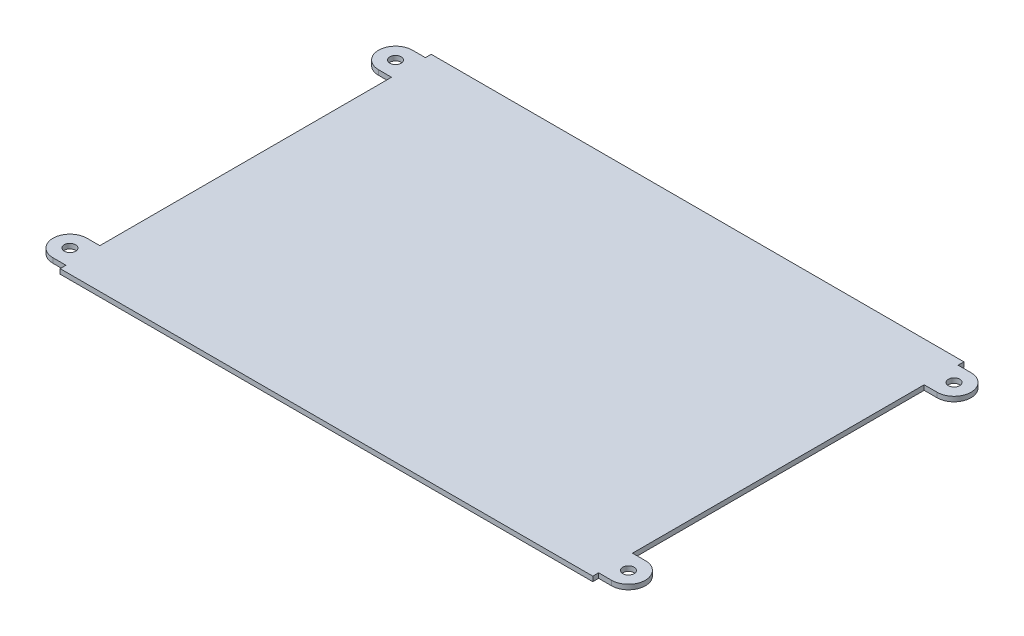
SolidWorks part; units mm, degrees
ref_plane "Front Plane" through (0, 0, 0) normal (0, 0, 1) x (1, 0, 0)
ref_plane "Top Plane" through (0, 0, 0) normal (0, 1, 0) x (1, 0, 0)
ref_plane "Right Plane" through (0, 0, 0) normal (1, 0, 0) x (0, 0, -1)
sketch "Sketch1" plane through (0, 0, 0) normal (0, 1, 0) x (1, 0, 0)
  line L0 (-82.45, -57.45) -> (82.45, -57.45)
  line L1 (-82.45, -57.45) -> (-82.45, 57.45)
  line L2 (82.45, -57.45) -> (82.45, 57.45)
  line L3 (-82.45, 57.45) -> (82.45, 57.45)
  line L4 (-82.45, -57.45) -> (82.45, 57.45) construction
  line L5 (82.45, -57.45) -> (-82.45, 57.45) construction
  point P1 (0, 0)
  dimension "D1" = 164.9
  dimension "D2" = 114.9
extrude "Boss-Extrude1" add sketch "Sketch1" along normal blind 1.5
sketch "Sketch2" plane through (0, 1.5, 0) normal (0, 1, 0) x (1, 0, 0)
  line L0 (-82.45, 57.45) -> (-82.45, -57.45) construction
  line L1 (-82.45, 55.65) -> (-82.45, 45.15)
  line L2 (-86.45, 55.65) -> (-82.45, 55.65)
  line L3 (-86.45, 45.15) -> (-82.45, 45.15)
  circle A0 centre (-86.45, 50.4) radius 1.75
  arc A1 (-86.45, 55.65) -> (-86.45, 45.15) centre (-86.45, 50.4) ccw
  circle A3 centre (-86.45, 50.4) radius 5.25 construction
  point P11 (-81.2, 50.4)
  dimension "D1" = 3.5
  dimension "D2" = 86.45
  dimension "D3" = 50.4
  dimension "D4" = 3.5
extrude "Boss-Extrude2" add sketch "Sketch2" against normal up to surface (1.5 mm away) up to face at (0, 0, 0)
pattern_linear "LPattern1" count 2 spacing 100.8 along (0, 0, 1) of "Boss-Extrude2"
mirror "Mirror1" about plane through (0, 0, 0) normal (1, 0, 0) of "LPattern1", "Boss-Extrude2"
